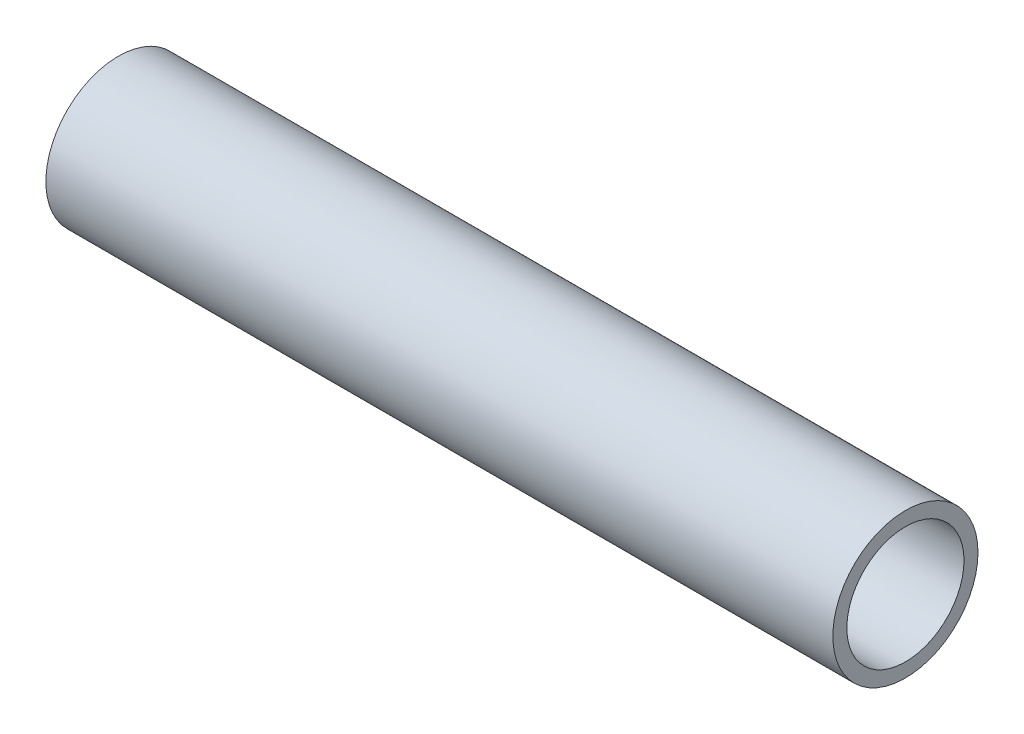
SolidWorks part; units mm, degrees
ref_plane "Front Plane" through (0, 0, 0) normal (0, 0, 1) x (1, 0, 0)
ref_plane "Top Plane" through (0, 0, 0) normal (0, 1, 0) x (1, 0, 0)
ref_plane "Right Plane" through (0, 0, 0) normal (1, 0, 0) x (0, 0, -1)
sketch "Sketch1" plane through (0, 0, 0) normal (1, 0, 0) x (0, 0, -1)
  circle A0 centre (0, 0) radius 21.082
  circle A1 centre (0, 0) radius 17.018
  dimension "D1" = 42.164
  dimension "D2" = 4.064
extrude "Boss-Extrude1" add sketch "Sketch1" along normal blind 228.6
